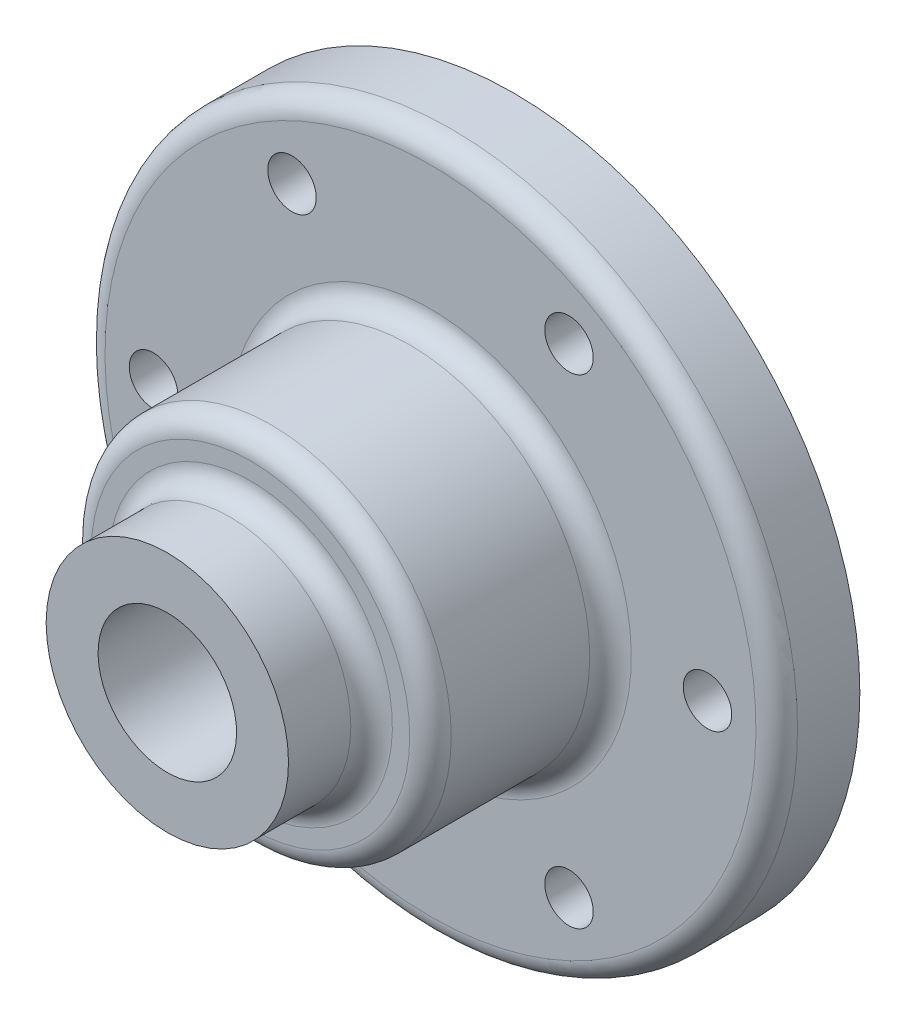
SolidWorks part; units mm, degrees
other "细节项目14"
other "细节项目15"
other "细节项目16"
ref_plane "Front Plane" through (0, 0, 0) normal (0, 0, 1) x (1, 0, 0)
ref_plane "Top Plane" through (0, 0, 0) normal (0, 1, 0) x (1, 0, 0)
ref_plane "Right Plane" through (0, 0, 0) normal (1, 0, 0) x (0, 0, -1)
sketch "Sketch1" plane through (0, 0, 0) normal (1, 0, 0) x (0, 0, -1)
  line L0 (0, 0) -> (-50, 0) construction
  line L1 (-50, 17.5) -> (-50, 10)
  line L2 (-50, 17.5) -> (-38, 17.5)
  line L3 (-38, 17.5) -> (-38, 26)
  line L4 (-38, 26) -> (-12, 26)
  line L5 (-12, 26) -> (-12, 50)
  line L6 (-12, 50) -> (0, 50)
  line L7 (0, 50) -> (0, 20)
  line L8 (0, 20) -> (-10, 20)
  line L9 (-10, 20) -> (-10, 10)
  line L10 (-10, 10) -> (-50, 10)
  dimension "D1" = 100
  dimension "D2" = 40
  dimension "D3" = 52
  dimension "D4" = 35
  dimension "D5" = 20
  dimension "D6" = 50
  dimension "D7" = 10
  dimension "D8" = 12
  dimension "D9" = 12
revolve "Revolve1" add sketch "Sketch1" angle 360 about L0
hole_wizard "Ø7.0 (7) Diameter Hole1" positions "Sketch2" profile "Sketch3" hole size "Ø7.0" standard "ANSI Metric" end condition through all
sketch "Sketch2" plane through (0, 0, 12) normal (0, 0, 1) x (1, 0, 0)
  circle A0 centre (0, 0) radius 40 construction
  point P5 (40, 0)
  dimension "D1" = 80
sketch "Sketch3" plane through (40, 0, 12) normal (1, 0, 0) x (0, -1, 0)
  line L0 (0, 0) -> (0, 12)
  line L1 (0, 12) -> (3.5, 12)
  line L2 (3.5, 12) -> (3.5, 0)
  line L5 (3.5, 0) -> (0, 0)
  line L11 (0, -6.35) -> (0, 107.95) construction
  dimension "Thru Hole Dia." = 7
  dimension "Thru Hole Depth" = 12
pattern_circular "CirPattern1" count 6 over 360 about axis through (0, 0, 0) along (0, 0, 1) of "Ø7.0 (7) Diameter Hole1"
fillet "Fillet1" radius 3 4 edges at (0, 17.5, 38) (0, 26, 38) (0, 26, 12) (0, 50, 12)
sketch "Groove Sketch" plane through (0, 0, 0) normal (0, 1, 0) x (0, 0, 1)
  line L0 (2.075, 27.25) -> (0, 27.25)
  line L1 (0, 27.25) -> (0, 30.8)
  line L2 (0, 30.8) -> (2.075, 30.8)
  line L3 (2.675, 30.2) -> (2.675, 27.85)
  line L4 (-50, 0) -> (50, 0) construction
  line L5 (0, -50) -> (0, 50) construction
  arc A0 (2.075, 30.8) -> (2.675, 30.2) centre (2.075, 30.2) cw
  arc A1 (2.675, 27.85) -> (2.075, 27.25) centre (2.075, 27.85) cw
  point P10 (0, 0)
  dimension "D1" = 2.675
  dimension "D2" = 0.6
  dimension "ID" = 54.5
  dimension "OD" = 61.6
revolve "O-Ring Groove" cut sketch "Groove Sketch" angle 360 about L4
